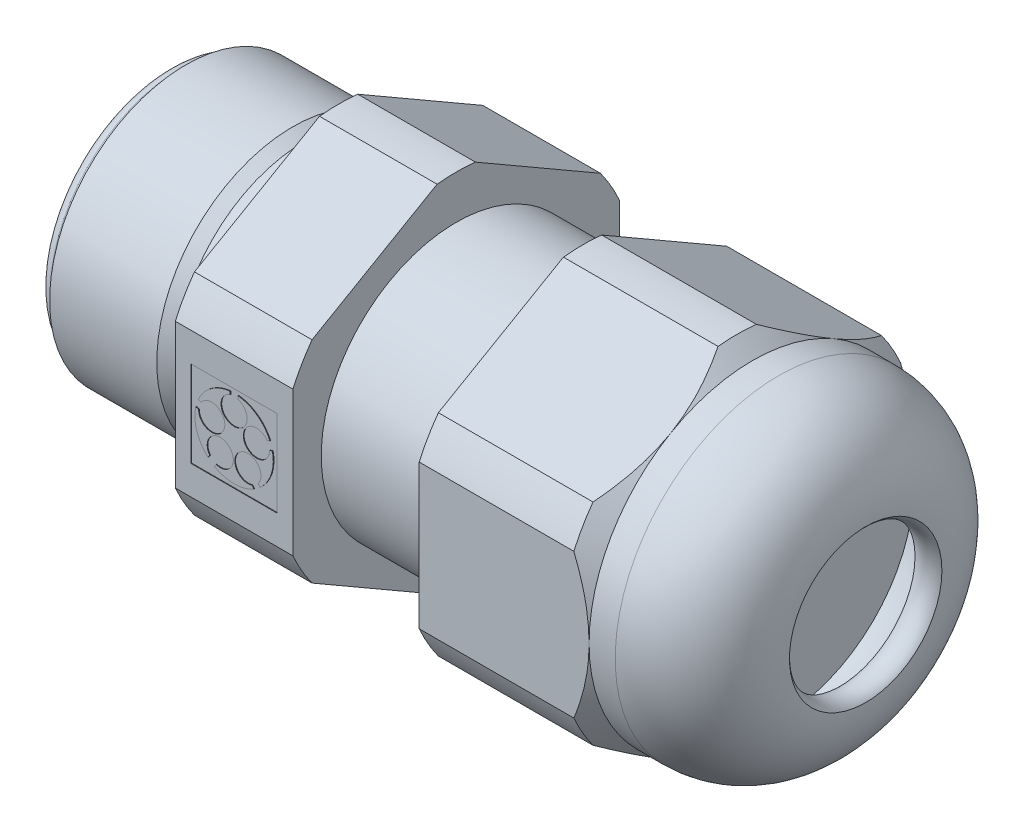
SolidWorks part; units mm, degrees
ref_plane "Face" through (0, 0, 0) normal (0, 0, 1) x (1, 0, 0)
ref_plane "Dessus" through (0, 0, 0) normal (0, 1, 0) x (1, 0, 0)
ref_plane "Droite" through (0, 0, 0) normal (1, 0, 0) x (0, 0, -1)
ref_plane "Plan1" through (0, 0, 0) normal (0, 0, 1) x (1, 0, 0)
sketch "Esquisse1" plane through (0, 0, 0) normal (0, 0, 1) x (1, 0, 0)
  line L0 (0, 5.4375) -> (0, 1.75)
  line L1 (0.5, 1.25) -> (28, 1.25)
  line L2 (28, 1.25) -> (28, 6.2)
  line L3 (28, 7.5) -> (26.8, 7.5)
  line L4 (26.8, 7.5) -> (24.3, 10)
  line L5 (24.3, 10) -> (19, 10)
  line L6 (19, 10) -> (19, 6.2)
  line L7 (19, 6.2) -> (13.2, 6.2)
  line L8 (13.2, 6.2) -> (13.2, 10)
  line L9 (13.2, 10) -> (7.8, 10)
  line L10 (7.8, 10) -> (7.8, 5.9375)
  line L11 (7.8, 5.9375) -> (6.24, 5.9375)
  line L12 (6.24, 5.9375) -> (5.6987, 6.25)
  line L13 (5.6987, 6.25) -> (0.78, 6.25)
  line L14 (0.78, 6.25) -> (0.78, 5.9375)
  line L15 (0.78, 5.9375) -> (0.5, 5.9375)
  line L16 (32, 0) -> (0, 0) construction
  arc A0 (0, 1.75) -> (0.5, 1.25) centre (0.5, 1.75) ccw
  arc A1 (28, 6.2) -> (30.6981, 3.6019) centre (28, 3.5) cw
  arc A2 (30.6981, 3.6019) -> (32, 3.5) centre (31.3851, 4.0118) ccw
  arc A3 (32, 3.5) -> (28, 7.5) centre (28, 3.5) ccw
  arc A4 (0.5, 5.9375) -> (0, 5.4375) centre (0.5, 5.4375) ccw
revolve "Révolution1" add sketch "Esquisse1" angle 360 about L16
cosmetic thread "Représentation de filetage1" parameters "D1"=5.5375, "D2"=11.875
cosmetic thread "Représentation de filetage2" parameters "D1"=5.46, "D2"=11.875
ref_plane "Plan2" through (7.8, 0, 0) normal (1, 0, 0) x (0, 0, -1)
sketch "Esquisse2" plane through (7.8, 0, 0) normal (1, 0, 0) x (0, 0, -1)
  line L0 (-15, -15) -> (15, -15)
  line L1 (15, -15) -> (15, 15)
  line L2 (15, 15) -> (-15, 15)
  line L3 (-15, 15) -> (-15, -15)
  line L4 (-7.5, 3.3151) -> (-7.5, -3.3151)
  line L5 (-6.621, -4.8376) -> (-0.879, -8.1527)
  line L6 (0.879, -8.1527) -> (6.621, -4.8376)
  line L7 (7.5, -3.3151) -> (7.5, 3.3151)
  line L8 (6.621, 4.8376) -> (0.879, 8.1527)
  line L9 (-0.879, 8.1527) -> (-6.621, 4.8376)
  arc A0 (-7.5, -3.3151) -> (-6.621, -4.8376) centre (0, 0) ccw
  arc A1 (-0.879, -8.1527) -> (0.879, -8.1527) centre (0, 0) ccw
  arc A2 (6.621, -4.8376) -> (7.5, -3.3151) centre (0, 0) ccw
  arc A3 (7.5, 3.3151) -> (6.621, 4.8376) centre (0, 0) ccw
  arc A4 (0.879, 8.1527) -> (-0.879, 8.1527) centre (0, 0) ccw
  arc A5 (-6.621, 4.8376) -> (-7.5, 3.3151) centre (0, 0) ccw
extrude "Enlèv. mat.-Extru.1" cut sketch "Esquisse2" along normal blind 32
ref_plane "Plan3" through (0, 0, 7.5) normal (0, 0, 1) x (1, 0, 0)
sketch "Esquisse3" plane through (0, 0, 7.5) normal (0, 0, 1) x (1, 0, 0)
  line L0 (8.52, -1.98) -> (12.48, -1.98)
  line L1 (12.48, -1.98) -> (12.48, 1.98)
  line L2 (12.48, 1.98) -> (8.52, 1.98)
  line L3 (8.52, 1.98) -> (8.52, -1.98)
  line L4 (9.3017, -1.3431) -> (9.3831, -1.231)
  line L5 (9.6744, -1.4426) -> (9.5929, -1.5547)
  line L6 (11.4071, -1.5547) -> (11.3256, -1.4426)
  line L7 (11.6169, -1.231) -> (11.6983, -1.3431)
  line L8 (12.2589, 0.3823) -> (12.1271, 0.3394)
  line L9 (12.0159, 0.6818) -> (12.1477, 0.7246)
  line L10 (10.68, 1.791) -> (10.68, 1.6524)
  line L11 (10.32, 1.6524) -> (10.32, 1.791)
  line L12 (8.8523, 0.7246) -> (8.9841, 0.6818)
  line L13 (8.8729, 0.3394) -> (8.7411, 0.3823)
  arc A0 (8.7411, 0.3823) -> (9.3017, -1.3431) centre (10.5, 0) ccw
  arc A1 (9.3831, -1.231) -> (9.6744, -1.4426) centre (9.8652, -0.8737) cw
  arc A2 (9.5929, -1.5547) -> (11.4071, -1.5547) centre (10.5, 0) ccw
  arc A3 (11.3256, -1.4426) -> (11.6169, -1.231) centre (11.1348, -0.8737) cw
  arc A4 (11.6983, -1.3431) -> (12.2589, 0.3823) centre (10.5, 0) ccw
  arc A5 (12.1271, 0.3394) -> (12.0159, 0.6818) centre (11.5271, 0.3337) cw
  arc A6 (12.1477, 0.7246) -> (10.68, 1.791) centre (10.5, 0) ccw
  arc A7 (10.68, 1.6524) -> (10.32, 1.6524) centre (10.5, 1.08) cw
  arc A8 (10.32, 1.791) -> (8.8523, 0.7246) centre (10.5, 0) ccw
  arc A9 (8.9841, 0.6818) -> (8.8729, 0.3394) centre (9.4729, 0.3337) cw
extrude "Enlèv. mat.-Extru.2" cut sketch "Esquisse3" against normal blind 0.03
